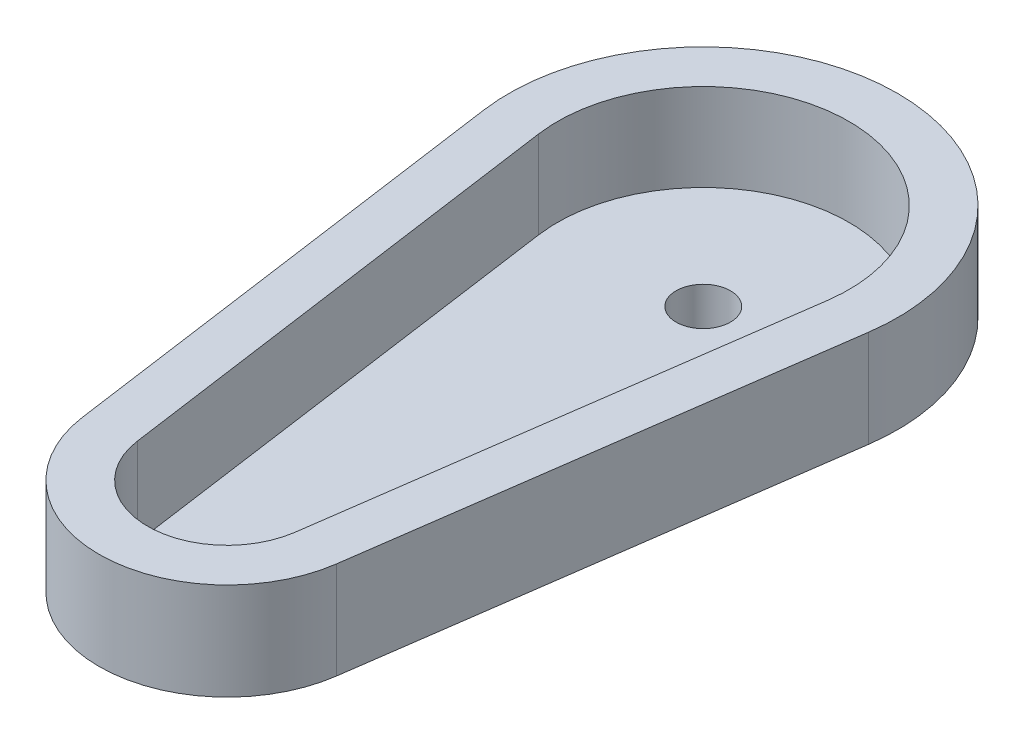
SolidWorks part; units mm, degrees
ref_plane "Front Plane" through (0, 0, 0) normal (0, 0, 1) x (1, 0, 0)
ref_plane "Top Plane" through (0, 0, 0) normal (0, 1, 0) x (1, 0, 0)
ref_plane "Right Plane" through (0, 0, 0) normal (1, 0, 0) x (0, 0, -1)
sketch "Sketch1" plane through (0, 0, 0) normal (0, 1, 0) x (1, 0, 0)
  line L0 (-7.4274, -1.0408) -> (-4.0603, -25.069)
  line L1 (7.4274, -1.0408) -> (4.0603, -25.069)
  arc A0 (-7.4274, -1.0408) -> (7.4274, -1.0408) centre (0, 0) cw
  arc A1 (-4.0603, -25.069) -> (4.0603, -25.069) centre (0, -24.5) ccw
  point P7 (0, 0)
  dimension "D1" = 7.5
  dimension "D2" = 4.1
  dimension "D3" = 24.5
extrude "Boss-Extrude1" add sketch "Sketch1" along normal blind 2.5
sketch "Sketch2" plane through (0, 0, 0) normal (0, -1, 0) x (1, 0, 0)
  line L4 (-7.4274, 1.0408) -> (-4.0603, 25.069) construction
  line L5 (4.0603, 25.069) -> (7.4274, 1.0408) construction
  line L6 (9.9032, 1.3878) -> (6.5361, 25.4159)
  line L7 (-6.5361, 25.4159) -> (-9.9032, 1.3878)
  line L8 (9.9032, 1.3878) -> (6.5361, 25.4159)
  line L9 (-6.5361, 25.4159) -> (-9.9032, 1.3878)
  line L10 (-7.4274, 1.0408) -> (-4.0603, 25.069)
  line L11 (4.0603, 25.069) -> (7.4274, 1.0408)
  arc A4 (-7.4274, 1.0408) -> (7.4274, 1.0408) centre (0, 0) ccw construction
  arc A5 (4.0603, 25.069) -> (-4.0603, 25.069) centre (0, 24.5) ccw construction
  arc A6 (-9.9032, 1.3878) -> (9.9032, 1.3878) centre (0, 0) ccw
  arc A7 (6.5361, 25.4159) -> (-6.5361, 25.4159) centre (0, 24.5) ccw
  arc A8 (-9.9032, 1.3878) -> (9.9032, 1.3878) centre (0, 0) ccw
  arc A9 (6.5361, 25.4159) -> (-6.5361, 25.4159) centre (0, 24.5) ccw
  arc A10 (-7.4274, 1.0408) -> (7.4274, 1.0408) centre (0, 0) ccw
  arc A11 (4.0603, 25.069) -> (-4.0603, 25.069) centre (0, 24.5) ccw
  dimension "D1" = 2.5
extrude "Boss-Extrude2" add sketch "Sketch2" against normal blind 7
sketch "Sketch3" plane through (0, 2.5, 0) normal (0, 1, 0) x (1, 0, 0)
  circle A0 centre (0, 0) radius 1.4
  circle A1 centre (0, -24.5) radius 1.4
  dimension "D1" = 2.8
extrude "Cut-Extrude1" cut sketch "Sketch3" against normal up to surface (2.5 mm away) up to face at (0, 0, 11.9759)
chamfer "Chamfer1" distance 2 angle 60 4 edges at (0, 0, 31.1) (-8.2197, 0, 13.4018) (8.2197, 0, 13.4018) (0, 0, -10)
